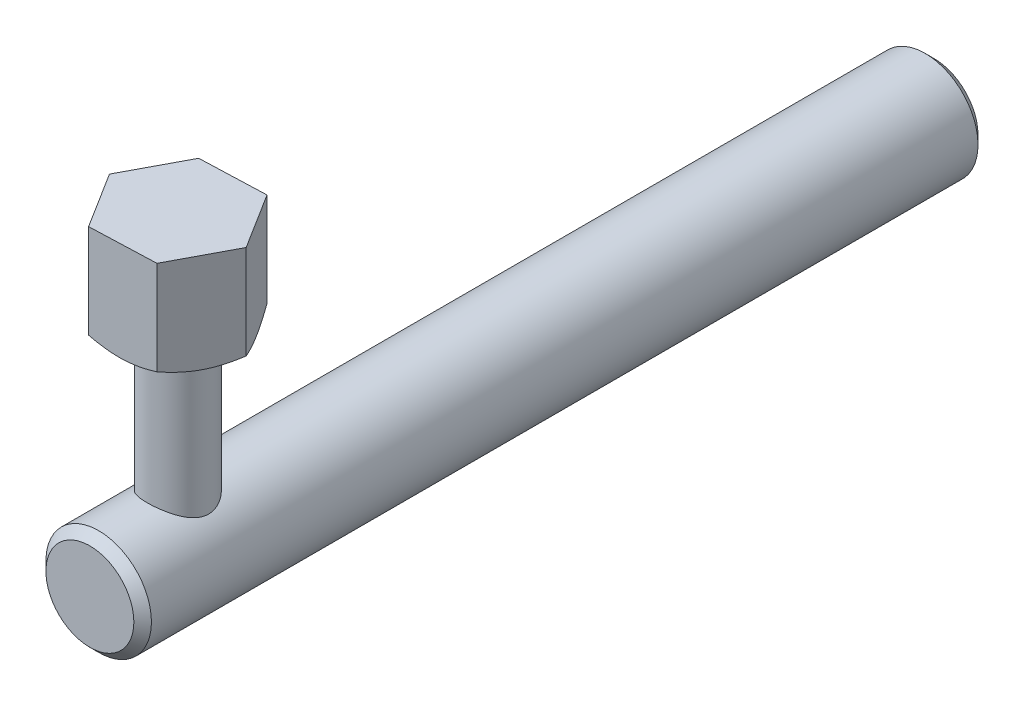
SolidWorks part; units mm, degrees
ref_plane "前视基准面" through (0, 0, 0) normal (0, 0, 1) x (1, 0, 0)
ref_plane "上视基准面" through (0, 0, 0) normal (0, 1, 0) x (1, 0, 0)
ref_plane "右视基准面" through (0, 0, 0) normal (1, 0, 0) x (0, 0, -1)
sketch "草图1" plane through (0, 0, 0) normal (0, 0, 1) x (1, 0, 0)
  circle A0 centre (0, 0) radius 3
  dimension "D1" = 6
extrude "凸台-拉伸1" add sketch "草图1" along normal blind 48
sketch "草图2" plane through (0, 0, 0) normal (0, 1, 0) x (1, 0, 0)
  line L0 (-3, -48) -> (3, -48) construction
  circle A0 centre (0, -43) radius 1.75
  dimension "D1" = 3.5
  dimension "D2" = 5
extrude "凸台-拉伸2" add sketch "草图2" along normal blind 10
sketch "草图3" plane through (0, 10, 0) normal (0, 1, 0) x (1, 0, 0)
  line L1 (-1.9936, -39.8206) -> (-3.7503, -43.1368)
  line L2 (-3.7503, -43.1368) -> (-1.7566, -46.3163)
  line L3 (-1.7566, -46.3163) -> (1.9936, -46.1794)
  line L4 (1.9936, -46.1794) -> (3.7503, -42.8632)
  line L5 (3.7503, -42.8632) -> (1.7566, -39.6837)
  line L6 (1.7566, -39.6837) -> (-1.9936, -39.8206)
  circle A0 centre (0, -43) radius 3.25 construction
  dimension "D1" = 6.5
extrude "凸台-拉伸3" add sketch "草图3" along normal blind 6.5
sketch "草图4" plane through (0, 0, 0) normal (1, 0, 0) x (0, 0, -1)
  line L0 (-44.75, 10) -> (-47.1186, 11.3675)
  line L2 (-47.1186, 11.3675) -> (-47.1186, 10)
  line L3 (-47.1186, 10) -> (-44.75, 10)
  dimension "D1" = 30
revolve "切除-旋转1" cut sketch "草图4" angle 360 about axis through (0, 10, 43) along (0, -1, 0)
chamfer "倒角1" distance 0.5 angle 45 2 edges at (3, 0, 0) (3, 0, 48)
